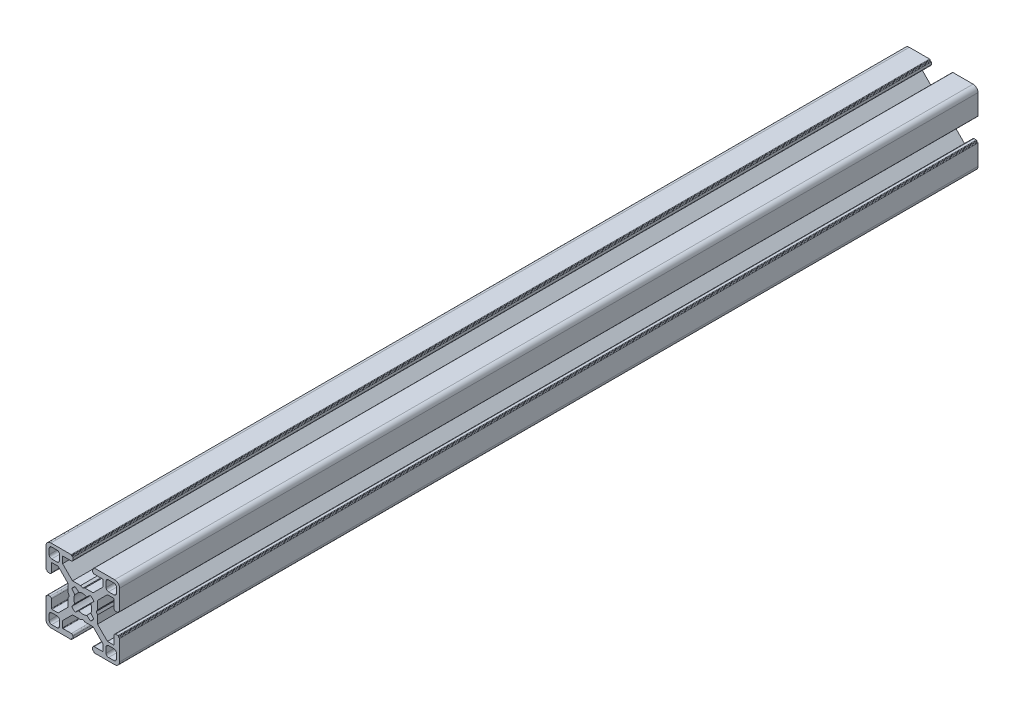
SolidWorks part; units mm, degrees
material "6061 Alloy"
ref_plane "Front" through (0, 0, 0) normal (0, 0, 1) x (1, 0, 0)
ref_plane "Top" through (0, 0, 0) normal (0, 1, 0) x (1, 0, 0)
ref_plane "Right" through (0, 0, 0) normal (1, 0, 0) x (0, 0, -1)
sketch "Sketch1" plane through (0, 0, 0) normal (0, 0, 1) x (1, 0, 0)
  line L0 (13.7, 12.7) -> (13.7, 10.5)
  line L1 (10.5, 9.5) -> (12.7, 9.5)
  line L2 (9.5, 12.7) -> (9.5, 10.5)
  line L3 (10.5, 13.7) -> (12.7, 13.7)
  line L4 (3.1359, 4.5184) -> (1.6001, 3.2806)
  line L5 (3.2806, 1.6001) -> (4.5053, 3.1547)
  line L6 (6.0045, 0.9) -> (5.4849, 0)
  line L7 (6.0045, 4.2045) -> (6.0045, 0.9)
  line L8 (0, -5.4849) -> (0.9, -6)
  line L9 (0.9, -6) -> (4.2045, -6)
  line L10 (4.2045, -6) -> (8.25, -10.05)
  line L11 (8.25, -10.05) -> (8.25, -12.6)
  line L12 (4.65, -12.8) -> (8.05, -12.8)
  line L13 (4.05, -14.3) -> (4.05, -13.4)
  line L14 (4.25, -14.5) -> (4.35, -14.5)
  line L15 (4.55, -14.8) -> (4.55, -14.7)
  line L16 (4.75, -15) -> (13, -15)
  line L17 (15, -13) -> (15, -4.75)
  line L18 (14.7, -4.55) -> (14.8, -4.55)
  line L19 (14.5, -4.35) -> (14.5, -4.25)
  line L20 (13.4, -4.05) -> (14.3, -4.05)
  line L21 (12.8, -8.05) -> (12.8, -4.65)
  line L22 (12.6, -8.25) -> (10.05, -8.25)
  line L23 (10.05, -8.25) -> (6.0045, -4.2045)
  line L24 (6.0045, -4.2045) -> (6.0045, -0.9)
  line L25 (6.0045, -0.9) -> (5.4849, 0)
  line L26 (10.05, 8.25) -> (6.0045, 4.2045)
  line L27 (12.6, 8.25) -> (10.05, 8.25)
  line L28 (12.8, 8.05) -> (12.8, 4.65)
  line L29 (13.4, 4.05) -> (14.3, 4.05)
  line L30 (14.5, 4.35) -> (14.5, 4.25)
  line L31 (14.7, 4.55) -> (14.8, 4.55)
  line L32 (15, 13) -> (15, 4.75)
  line L33 (4.75, 15) -> (13, 15)
  line L34 (4.55, 14.8) -> (4.55, 14.7)
  line L35 (4.25, 14.5) -> (4.35, 14.5)
  line L36 (4.05, 14.3) -> (4.05, 13.4)
  line L37 (4.65, 12.8) -> (8.05, 12.8)
  line L38 (8.25, 10.05) -> (8.25, 12.6)
  line L39 (4.2045, 6) -> (8.25, 10.05)
  line L40 (0.9, 6) -> (4.2045, 6)
  line L41 (0, 5.4849) -> (0.9, 6)
  line L42 (-13.7, -12.7) -> (-13.7, -10.5)
  line L43 (-10.5, -9.5) -> (-12.7, -9.5)
  line L44 (-9.5, -12.7) -> (-9.5, -10.5)
  line L45 (-10.5, -13.7) -> (-12.7, -13.7)
  line L46 (-3.1359, -4.5184) -> (-1.6001, -3.2806)
  line L47 (-3.2806, -1.6001) -> (-4.5053, -3.1547)
  line L48 (0, 5.4849) -> (-0.9, 6)
  line L49 (-0.9, 6) -> (-4.2045, 6)
  line L50 (-4.2045, 6) -> (-8.25, 10.05)
  line L51 (-8.25, 10.05) -> (-8.25, 12.6)
  line L52 (-4.65, 12.8) -> (-8.05, 12.8)
  line L53 (-4.05, 14.3) -> (-4.05, 13.4)
  line L54 (-4.25, 14.5) -> (-4.35, 14.5)
  line L55 (-4.55, 14.8) -> (-4.55, 14.7)
  line L56 (-4.75, 15) -> (-13, 15)
  line L57 (-15, 13) -> (-15, 4.75)
  line L58 (-14.7, 4.55) -> (-14.8, 4.55)
  line L59 (-14.5, 4.35) -> (-14.5, 4.25)
  line L60 (-13.4, 4.05) -> (-14.3, 4.05)
  line L61 (-12.8, 8.05) -> (-12.8, 4.65)
  line L62 (-12.6, 8.25) -> (-10.05, 8.25)
  line L63 (-10.05, 8.25) -> (-6.0045, 4.2045)
  line L64 (-6.0045, -0.9) -> (-5.4849, 0)
  line L65 (-6.0045, -4.2045) -> (-6.0045, -0.9)
  line L66 (-10.05, -8.25) -> (-6.0045, -4.2045)
  line L67 (-12.6, -8.25) -> (-10.05, -8.25)
  line L68 (-12.8, -8.05) -> (-12.8, -4.65)
  line L69 (-13.4, -4.05) -> (-14.3, -4.05)
  line L70 (-14.5, -4.35) -> (-14.5, -4.25)
  line L71 (-14.7, -4.55) -> (-14.8, -4.55)
  line L72 (-15, -13) -> (-15, -4.75)
  line L73 (-4.75, -15) -> (-13, -15)
  line L74 (-4.55, -14.8) -> (-4.55, -14.7)
  line L75 (-4.25, -14.5) -> (-4.35, -14.5)
  line L76 (-4.05, -14.3) -> (-4.05, -13.4)
  line L77 (3.2806, -1.6001) -> (4.5053, -3.1547)
  line L78 (3.1359, -4.5184) -> (1.6001, -3.2806)
  line L79 (-4.65, -12.8) -> (-8.05, -12.8)
  line L80 (-8.25, -10.05) -> (-8.25, -12.6)
  line L81 (-4.2045, -6) -> (-8.25, -10.05)
  line L82 (-0.9, -6) -> (-4.2045, -6)
  line L83 (0, -5.4849) -> (-0.9, -6)
  line L84 (10.5, -13.7) -> (12.7, -13.7)
  line L85 (9.5, -12.7) -> (9.5, -10.5)
  line L86 (10.5, -9.5) -> (12.7, -9.5)
  line L87 (13.7, -12.7) -> (13.7, -10.5)
  line L88 (-6.0045, 4.2045) -> (-6.0045, 0.9)
  line L89 (-6.0045, 0.9) -> (-5.4849, 0)
  line L90 (-3.2806, 1.6001) -> (-4.5053, 3.1547)
  line L91 (-3.1359, 4.5184) -> (-1.6001, 3.2806)
  line L92 (-10.5, 13.7) -> (-12.7, 13.7)
  line L93 (-9.5, 12.7) -> (-9.5, 10.5)
  line L94 (-10.5, 9.5) -> (-12.7, 9.5)
  line L95 (-13.7, 12.7) -> (-13.7, 10.5)
  line L96 (-23.4857, 0) -> (20.9308, 0) construction
  line L97 (0, 17.9563) -> (0, -17.361) construction
  arc A0 (13.7, 12.7) -> (12.7, 13.7) centre (12.7, 12.7) ccw
  arc A1 (12.7, 9.5) -> (13.7, 10.5) centre (12.7, 10.5) ccw
  arc A2 (9.5, 10.5) -> (10.5, 9.5) centre (10.5, 10.5) ccw
  arc A3 (10.5, 13.7) -> (9.5, 12.7) centre (10.5, 12.7) ccw
  arc A4 (1.6001, 3.2806) -> (-1.6001, 3.2806) centre (0, 0) ccw
  arc A5 (8.25, -12.6) -> (8.05, -12.8) centre (8.05, -12.6) cw
  arc A6 (4.65, -12.8) -> (4.05, -13.4) centre (4.65, -13.4) ccw
  arc A7 (4.05, -14.3) -> (4.25, -14.5) centre (4.25, -14.3) ccw
  arc A8 (4.35, -14.5) -> (4.55, -14.7) centre (4.35, -14.7) cw
  arc A9 (4.55, -14.8) -> (4.75, -15) centre (4.75, -14.8) ccw
  arc A10 (13, -15) -> (15, -13) centre (13, -13) ccw
  arc A11 (15, -4.75) -> (14.8, -4.55) centre (14.8, -4.75) ccw
  arc A12 (14.7, -4.55) -> (14.5, -4.35) centre (14.7, -4.35) cw
  arc A13 (14.5, -4.25) -> (14.3, -4.05) centre (14.3, -4.25) ccw
  arc A14 (13.4, -4.05) -> (12.8, -4.65) centre (13.4, -4.65) ccw
  arc A15 (12.8, -8.05) -> (12.6, -8.25) centre (12.6, -8.05) cw
  arc A16 (4.5053, 3.1547) -> (3.1359, 4.5184) centre (0, 0) ccw
  arc A17 (12.8, 8.05) -> (12.6, 8.25) centre (12.6, 8.05) ccw
  arc A18 (13.4, 4.05) -> (12.8, 4.65) centre (13.4, 4.65) cw
  arc A19 (14.5, 4.25) -> (14.3, 4.05) centre (14.3, 4.25) cw
  arc A20 (14.7, 4.55) -> (14.5, 4.35) centre (14.7, 4.35) ccw
  arc A21 (15, 4.75) -> (14.8, 4.55) centre (14.8, 4.75) cw
  arc A22 (13, 15) -> (15, 13) centre (13, 13) cw
  arc A23 (4.55, 14.8) -> (4.75, 15) centre (4.75, 14.8) cw
  arc A24 (4.35, 14.5) -> (4.55, 14.7) centre (4.35, 14.7) ccw
  arc A25 (4.05, 14.3) -> (4.25, 14.5) centre (4.25, 14.3) cw
  arc A26 (4.65, 12.8) -> (4.05, 13.4) centre (4.65, 13.4) cw
  arc A27 (8.25, 12.6) -> (8.05, 12.8) centre (8.05, 12.6) ccw
  arc A28 (-13.7, -12.7) -> (-12.7, -13.7) centre (-12.7, -12.7) ccw
  arc A29 (-12.7, -9.5) -> (-13.7, -10.5) centre (-12.7, -10.5) ccw
  arc A30 (-9.5, -10.5) -> (-10.5, -9.5) centre (-10.5, -10.5) ccw
  arc A31 (-10.5, -13.7) -> (-9.5, -12.7) centre (-10.5, -12.7) ccw
  arc A32 (-4.5053, -3.1547) -> (-3.1359, -4.5184) centre (0, 0) ccw
  arc A33 (-3.2806, 1.6001) -> (-3.2806, -1.6001) centre (0, 0) ccw
  arc A34 (-8.25, 12.6) -> (-8.05, 12.8) centre (-8.05, 12.6) cw
  arc A35 (-4.65, 12.8) -> (-4.05, 13.4) centre (-4.65, 13.4) ccw
  arc A36 (-4.05, 14.3) -> (-4.25, 14.5) centre (-4.25, 14.3) ccw
  arc A37 (-4.35, 14.5) -> (-4.55, 14.7) centre (-4.35, 14.7) cw
  arc A38 (-4.55, 14.8) -> (-4.75, 15) centre (-4.75, 14.8) ccw
  arc A39 (-13, 15) -> (-15, 13) centre (-13, 13) ccw
  arc A40 (-15, 4.75) -> (-14.8, 4.55) centre (-14.8, 4.75) ccw
  arc A41 (-14.7, 4.55) -> (-14.5, 4.35) centre (-14.7, 4.35) cw
  arc A42 (-14.5, 4.25) -> (-14.3, 4.05) centre (-14.3, 4.25) ccw
  arc A43 (-13.4, 4.05) -> (-12.8, 4.65) centre (-13.4, 4.65) ccw
  arc A44 (-12.8, 8.05) -> (-12.6, 8.25) centre (-12.6, 8.05) cw
  arc A45 (-4.5053, 3.1547) -> (-3.1359, 4.5184) centre (0, 0) cw
  arc A46 (-12.8, -8.05) -> (-12.6, -8.25) centre (-12.6, -8.05) ccw
  arc A47 (-13.4, -4.05) -> (-12.8, -4.65) centre (-13.4, -4.65) cw
  arc A48 (-14.5, -4.25) -> (-14.3, -4.05) centre (-14.3, -4.25) cw
  arc A49 (3.2806, 1.6001) -> (3.2806, -1.6001) centre (0, 0) cw
  arc A50 (4.5053, -3.1547) -> (3.1359, -4.5184) centre (0, 0) cw
  arc A51 (1.6001, -3.2806) -> (-1.6001, -3.2806) centre (0, 0) cw
  arc A52 (-14.7, -4.55) -> (-14.5, -4.35) centre (-14.7, -4.35) ccw
  arc A53 (-15, -4.75) -> (-14.8, -4.55) centre (-14.8, -4.75) cw
  arc A54 (-13, -15) -> (-15, -13) centre (-13, -13) cw
  arc A55 (-4.55, -14.8) -> (-4.75, -15) centre (-4.75, -14.8) cw
  arc A56 (10.5, -13.7) -> (9.5, -12.7) centre (10.5, -12.7) cw
  arc A57 (9.5, -10.5) -> (10.5, -9.5) centre (10.5, -10.5) cw
  arc A58 (12.7, -9.5) -> (13.7, -10.5) centre (12.7, -10.5) cw
  arc A59 (13.7, -12.7) -> (12.7, -13.7) centre (12.7, -12.7) cw
  arc A60 (-4.35, -14.5) -> (-4.55, -14.7) centre (-4.35, -14.7) ccw
  arc A61 (-4.05, -14.3) -> (-4.25, -14.5) centre (-4.25, -14.3) cw
  arc A62 (-4.65, -12.8) -> (-4.05, -13.4) centre (-4.65, -13.4) cw
  arc A63 (-8.25, -12.6) -> (-8.05, -12.8) centre (-8.05, -12.6) ccw
  arc A64 (-10.5, 13.7) -> (-9.5, 12.7) centre (-10.5, 12.7) cw
  arc A65 (-9.5, 10.5) -> (-10.5, 9.5) centre (-10.5, 10.5) cw
  arc A66 (-12.7, 9.5) -> (-13.7, 10.5) centre (-12.7, 10.5) cw
  arc A67 (-13.7, 12.7) -> (-12.7, 13.7) centre (-12.7, 12.7) cw
  point P81 (15, 15)
  point P82 (0, 15)
  point P203 (0, -15)
  point P204 (15, -15)
  point P206 (0, 0)
  point P207 (15, 0)
  point P219 (-15, 0)
  point P220 (-15, -15)
  point P221 (-15, 15)
extrude "Base-Extrude" add sketch "Sketch1" against normal blind 350
sketch "草图2" plane through (15, 0, 0) normal (1, 0, 0) x (0, 0, -1)
  line L0 (0, 15) -> (30, -15)
  line L1 (350, -15) -> (0, -15) construction
  line L2 (0, 4.75) -> (0, 13) construction
  line L3 (0, 15) -> (0, -15)
  line L4 (0, -15) -> (30, -15)
  line L5 (-13.0087, 11.9543) -> (-11.263, 12.8943)
  dimension "D1" = 45
